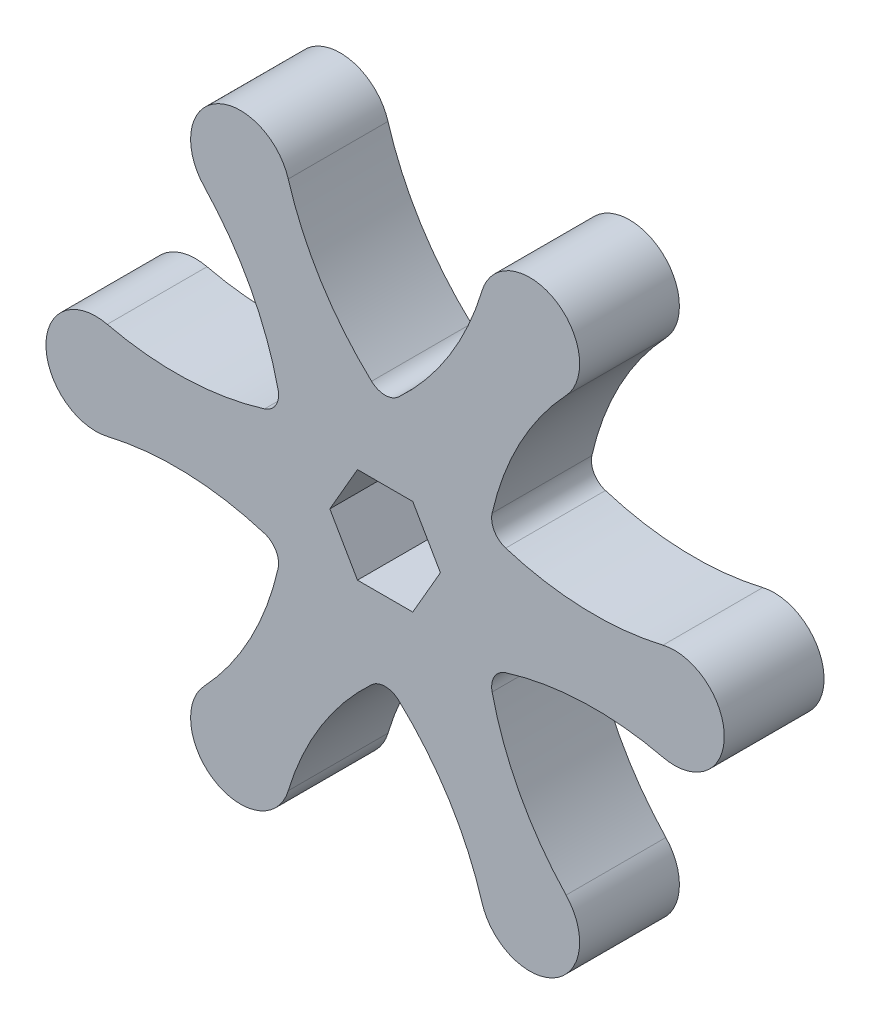
SolidWorks part; units mm, degrees
ref_plane "Plan de face" through (0, 0, 0) normal (1, 0, 0) x (0, 1, 0)
ref_plane "Plan de dessus" through (0, 0, 0) normal (0, 0, 1) x (0, 1, 0)
ref_plane "Plan de droite" through (0, 0, 0) normal (0, 1, 0) x (-1, 0, 0)
sketch "Esquisse1" plane through (0, 0, 0) normal (0, 0, 1) x (0, 1, 0)
  line L0 (0, 0) -> (0, 32.4301) construction
  line L1 (0, 5.5426) -> (-4.8, 2.7713)
  line L2 (-4.8, 2.7713) -> (-4.8, -2.7713)
  line L3 (-4.8, -2.7713) -> (0, -5.5426)
  line L4 (0, -5.5426) -> (4.8, -2.7713)
  line L5 (4.8, -2.7713) -> (4.8, 2.7713)
  line L6 (4.8, 2.7713) -> (0, 5.5426)
  line L7 (25.1147, 14.5) -> (0, 0) construction
  circle A0 centre (0, 0) radius 10
  circle A1 centre (0, 0) radius 4.8 construction
  circle A2 centre (0, 29) radius 5
  arc A3 (4.8665, 27.8522) -> (8.5163, 5.2414) centre (34.0653, 20.9655) ccw
  arc A4 (-4.8665, 27.8522) -> (-8.5163, 5.2414) centre (-34.0653, 20.9655) cw
  circle A5 centre (25.1147, 14.5) radius 5
  arc A6 (21.6875, 18.1406) -> (0.281, 9.9961) centre (1.124, 39.9842) cw
  arc A7 (26.554, 9.7116) -> (8.7973, -4.7547) centre (35.1893, -19.0187) ccw
  circle A8 centre (25.1147, -14.5) radius 5
  arc A9 (26.554, -9.7116) -> (8.7973, 4.7547) centre (35.1893, 19.0187) cw
  arc A10 (21.6875, -18.1406) -> (0.281, -9.9961) centre (1.124, -39.9842) ccw
  circle A11 centre (0, -29) radius 5
  arc A12 (4.8665, -27.8522) -> (8.5163, -5.2414) centre (34.0653, -20.9655) cw
  arc A13 (-4.8665, -27.8522) -> (-8.5163, -5.2414) centre (-34.0653, -20.9655) ccw
  circle A14 centre (-25.1147, -14.5) radius 5
  arc A15 (-21.6875, -18.1406) -> (-0.281, -9.9961) centre (-1.124, -39.9842) cw
  arc A16 (-26.554, -9.7116) -> (-8.7973, 4.7547) centre (-35.1893, 19.0187) ccw
  circle A17 centre (-25.1147, 14.5) radius 5
  arc A18 (-26.554, 9.7116) -> (-8.7973, -4.7547) centre (-35.1893, -19.0187) cw
  arc A19 (-21.6875, 18.1406) -> (-0.281, 9.9961) centre (-1.124, 39.9842) ccw
  point P62 (0, 0)
  dimension "D2" = 20
  dimension "D3" = 10
  dimension "D5" = 30
  dimension "D1" = 9.6
  dimension "D4" = 29
  dimension "D7" = 29
  dimension "D8" = 60
  dimension "D6" = 6
extrude "Boss.-Extru.1" add sketch "Esquisse1" along normal blind 10 contours A11 | A15 A13 A11 A12 A10 A0 | A8 | A12 A10 A8 A9 A7 A0 | A14 | A18 A16 A14 A15 A13 A0 | A19 A17 A18 A16 A0 A4 | A17 | A16 A18 A0 | A13 A15 A0 | A0 L6 L5 L4 L3 L2 L1 | A19 A4 A0 | A4 A19 A0 A6 A3 A2 | A9 A7 A5 A6 A3 A0 | A3 A6 A0 | A7 A9 A0 | A10 A12 A0 | A5 | A2
fillet "Congé1" radius 2 6 edges at (0, 11.9883, 5) (-10.3821, 5.9941, 5) (-10.3821, -5.9941, 5) (0, -11.9883, 5) (10.3821, -5.9941, 5) (10.3821, 5.9941, 5)
sketch "Esquisse2" plane through (0, 0, 0) normal (0, 0, -1) x (1, 0, 0)
  line L0 (0, 0) -> (0, 11.7638) construction
  line L1 (0, 9.5) -> (-2, 8.2614)
  line L2 (-2, 8.2614) -> (0, 7.5)
  line L3 (0, 0) -> (-9.5, 0) construction
  line L4 (-9.5, 0) -> (-8.2614, -2)
  line L5 (-8.2614, -2) -> (-7.5, 0)
  arc A0 (-7.5, 0) -> (0, 7.5) centre (0, 0) ccw
  arc A1 (-9.5, 0) -> (0, 9.5) centre (0, 0) ccw
  arc A2 (-8.5, 0) -> (-2, 8.2614) centre (0, 0) ccw construction
  circle A3 centre (0, 0) radius 9.5 construction
  circle A4 centre (0, 0) radius 7.5 construction
  text T0 "<b>+</b>" font "Century Gothic" height 5
  dimension "D2" = 15
  dimension "D3" = 17
  dimension "D4" = 2
  dimension "D5" = 2
  dimension "D1" = 2
extrude "Enlèv. mat.-Extru.1" cut sketch "Esquisse2" against normal blind 1
